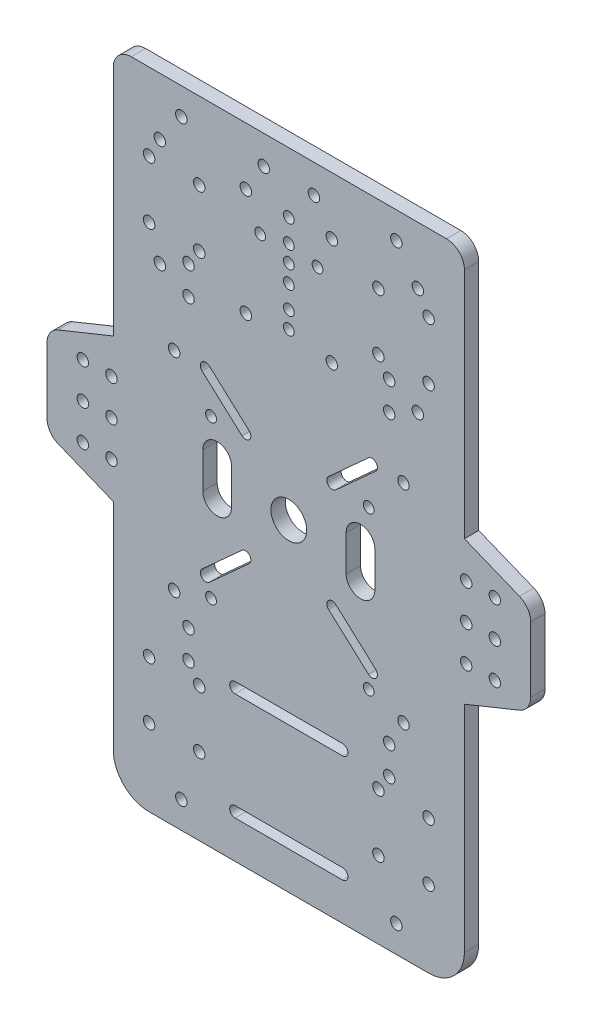
SolidWorks part; units mm, degrees
ref_plane "前视基准面" through (0, 0, 0) normal (0, 0, 1) x (1, 0, 0)
ref_plane "上视基准面" through (0, 0, 0) normal (0, 1, 0) x (1, 0, 0)
ref_plane "右视基准面" through (0, 0, 0) normal (1, 0, 0) x (0, 0, -1)
sketch "草图1" plane through (0, 0, 0) normal (0, 0, 1) x (1, 0, 0)
  line L0 (71.9587, 87.9417) -> (71.9587, 97.9417)
  line L1 (63.9587, 97.9417) -> (63.9587, 87.9417)
  line L2 (31.9587, 87.9417) -> (31.9587, 97.9417)
  line L3 (23.9587, 97.9417) -> (23.9587, 87.9417)
  line L4 (61.0638, 106.7939) -> (72.1786, 116.8666)
  line L5 (70.164, 119.0896) -> (59.0492, 109.0168)
  line L6 (36.8682, 109.0168) -> (25.7534, 119.0896)
  line L7 (23.7389, 116.8666) -> (34.8537, 106.7939)
  line L8 (34.8537, 79.0896) -> (23.7389, 69.0168)
  line L9 (25.7534, 66.7939) -> (36.8682, 76.8666)
  line L10 (59.0492, 76.8666) -> (70.164, 66.7939)
  line L11 (72.1786, 69.0168) -> (61.0638, 79.0896)
  line L12 (32.9587, 43.4417) -> (62.9587, 43.4417)
  line L13 (62.9587, 46.4417) -> (32.9587, 46.4417)
  line L14 (32.9587, 13.4417) -> (62.9587, 13.4417)
  line L15 (62.9587, 16.4417) -> (32.9587, 16.4417)
  line L16 (-16.4198, 79.1763) -> (-1.0413, 72.9417)
  line L17 (-19.5413, 102.0735) -> (-19.5413, 83.81)
  line L18 (-1.0413, 112.9417) -> (-16.4198, 106.7072)
  line L19 (-1.0413, 177.9417) -> (-1.0413, 112.9417)
  line L20 (91.9587, 182.9417) -> (3.9587, 182.9417)
  line L21 (96.9587, 112.9417) -> (96.9587, 177.9417)
  line L22 (112.3373, 106.7072) -> (96.9587, 112.9417)
  line L23 (115.4587, 83.81) -> (115.4587, 102.0735)
  line L24 (96.9587, 72.9417) -> (112.3373, 79.1763)
  line L25 (96.9587, 12.9417) -> (96.9587, 72.9417)
  line L26 (8.9587, 2.9417) -> (86.9587, 2.9417)
  line L27 (-1.0413, 72.9417) -> (-1.0413, 12.9417)
  arc A0 (96.9587, 177.9417) -> (91.9587, 182.9417) centre (91.9587, 177.9417) ccw
  arc A1 (115.4587, 102.0735) -> (112.3373, 106.7072) centre (110.4587, 102.0735) ccw
  arc A2 (112.3373, 79.1763) -> (115.4587, 83.81) centre (110.4587, 83.81) ccw
  arc A3 (86.9587, 2.9417) -> (96.9587, 12.9417) centre (86.9587, 12.9417) ccw
  arc A4 (-1.0413, 12.9417) -> (8.9587, 2.9417) centre (8.9587, 12.9417) ccw
  arc A5 (-19.5413, 83.81) -> (-16.4198, 79.1763) centre (-14.5413, 83.81) ccw
  arc A6 (-16.4198, 106.7072) -> (-19.5413, 102.0735) centre (-14.5413, 102.0735) ccw
  arc A7 (3.9587, 182.9417) -> (-1.0413, 177.9417) centre (3.9587, 177.9417) ccw
  circle A8 centre (22.9587, 161.4417) radius 1.6
  circle A9 centre (72.9587, 145.4417) radius 1.6
  circle A10 centre (72.9587, 24.4417) radius 1.6
  circle A11 centre (72.9587, 40.4417) radius 1.6
  circle A12 centre (86.9587, 40.4417) radius 1.6
  circle A13 centre (86.9587, 145.4417) radius 1.6
  circle A14 centre (86.9587, 161.4417) radius 1.6
  circle A15 centre (72.9587, 161.4417) radius 1.6
  circle A16 centre (22.9587, 40.4417) radius 1.6
  circle A17 centre (8.9587, 145.4417) radius 1.6
  circle A18 centre (8.9587, 161.4417) radius 1.6
  circle A19 centre (22.9587, 145.4417) radius 1.6
  circle A20 centre (86.9587, 24.4417) radius 1.6
  circle A21 centre (8.9587, 24.4417) radius 1.6
  circle A22 centre (8.9587, 40.4417) radius 1.6
  circle A23 centre (22.9587, 24.4417) radius 1.6
  circle A24 centre (40.9587, 174.9417) radius 1.6
  circle A25 centre (75.9587, 140.9417) radius 1.6
  circle A26 centre (54.9587, 174.9417) radius 1.6
  circle A27 centre (19.9587, 52.9417) radius 1.6
  circle A28 centre (19.9587, 44.9417) radius 1.6
  circle A29 centre (75.9587, 44.9417) radius 1.6
  circle A30 centre (75.9587, 132.9417) radius 1.6
  circle A31 centre (19.9587, 132.9417) radius 1.6
  circle A32 centre (19.9587, 140.9417) radius 1.6
  circle A33 centre (75.9587, 52.9417) radius 1.6
  circle A34 centre (35.9587, 136.9417) radius 1.6
  circle A35 centre (97.4587, 82.9417) radius 1.6
  circle A36 centre (105.4587, 82.9417) radius 1.6
  circle A37 centre (97.4587, 92.9417) radius 1.6
  circle A38 centre (105.4587, 92.9417) radius 1.6
  circle A39 centre (-9.5413, 82.9417) radius 1.6
  circle A40 centre (-1.5413, 82.9417) radius 1.6
  circle A41 centre (-1.5413, 92.9417) radius 1.6
  circle A42 centre (-9.5413, 92.9417) radius 1.6
  arc A43 (63.9587, 87.9417) -> (71.9587, 87.9417) centre (67.9587, 87.9417) ccw
  arc A44 (71.9587, 97.9417) -> (63.9587, 97.9417) centre (67.9587, 97.9417) ccw
  arc A45 (23.9587, 87.9417) -> (31.9587, 87.9417) centre (27.9587, 87.9417) ccw
  arc A46 (31.9587, 97.9417) -> (23.9587, 97.9417) centre (27.9587, 97.9417) ccw
  arc A47 (59.0492, 109.0168) -> (61.0638, 106.7939) centre (60.0565, 107.9053) ccw
  arc A48 (72.1786, 116.8666) -> (70.164, 119.0896) centre (71.1713, 117.9781) ccw
  arc A49 (34.8537, 106.7939) -> (36.8682, 109.0168) centre (35.861, 107.9053) ccw
  arc A50 (25.7534, 119.0896) -> (23.7389, 116.8666) centre (24.7462, 117.9781) ccw
  arc A51 (36.8682, 76.8666) -> (34.8537, 79.0896) centre (35.861, 77.9781) ccw
  arc A52 (23.7389, 69.0168) -> (25.7534, 66.7939) centre (24.7462, 67.9053) ccw
  arc A53 (61.0638, 79.0896) -> (59.0492, 76.8666) centre (60.0565, 77.9781) ccw
  arc A54 (70.164, 66.7939) -> (72.1786, 69.0168) centre (71.1713, 67.9053) ccw
  circle A55 centre (-1.5413, 102.9417) radius 1.6
  circle A56 centre (-9.5413, 102.9417) radius 1.6
  circle A57 centre (83.9587, 136.9417) radius 1.6
  circle A58 centre (59.9587, 136.9417) radius 1.6
  circle A59 centre (59.9587, 166.9417) radius 1.6
  circle A60 centre (15.9587, 117.9417) radius 1.6
  circle A61 centre (35.9587, 166.9417) radius 1.6
  circle A62 centre (11.9587, 136.9417) radius 1.6
  circle A63 centre (11.9587, 166.9417) radius 1.6
  circle A64 centre (83.9587, 166.9417) radius 1.6
  circle A65 centre (105.4587, 102.9417) radius 1.6
  circle A66 centre (97.4587, 102.9417) radius 1.6
  arc A67 (32.9587, 46.4417) -> (32.9587, 43.4417) centre (32.9587, 44.9417) ccw
  arc A68 (62.9587, 43.4417) -> (62.9587, 46.4417) centre (62.9587, 44.9417) ccw
  arc A69 (32.9587, 16.4417) -> (32.9587, 13.4417) centre (32.9587, 14.9417) ccw
  arc A70 (62.9587, 13.4417) -> (62.9587, 16.4417) centre (62.9587, 14.9417) ccw
  circle A71 centre (47.9587, 92.9417) radius 5
  circle A72 centre (79.9587, 117.9417) radius 1.6
  circle A73 centre (79.9587, 59.9417) radius 1.6
  circle A74 centre (15.9587, 59.9417) radius 1.6
  circle A75 centre (77.9587, 175.4417) radius 1.6
  circle A76 centre (17.9587, 175.4417) radius 1.6
  circle A77 centre (17.9587, 10.4417) radius 1.6
  circle A78 centre (77.9587, 10.4417) radius 1.6
  circle A79 centre (26.2462, 107.1852) radius 1.5
  circle A80 centre (26.2462, 63.1852) radius 1.5
  circle A81 centre (70.2462, 63.1852) radius 1.5
  circle A82 centre (70.2462, 107.1852) radius 1.5
  circle A83 centre (47.9602, 166.1201) radius 1.5
  circle A84 centre (47.9602, 150.1201) radius 1.5
  circle A85 centre (39.9602, 158.1201) radius 1.5
  circle A86 centre (55.9602, 158.1201) radius 1.5
  circle A87 centre (47.9602, 159.7923) radius 1.5
  circle A88 centre (47.9602, 143.7923) radius 1.5
  circle A89 centre (47.9602, 155.0464) radius 1.5
  circle A90 centre (47.9602, 139.0464) radius 1.5
extrude "凸台-拉伸1" add sketch "草图1" along normal blind 4
